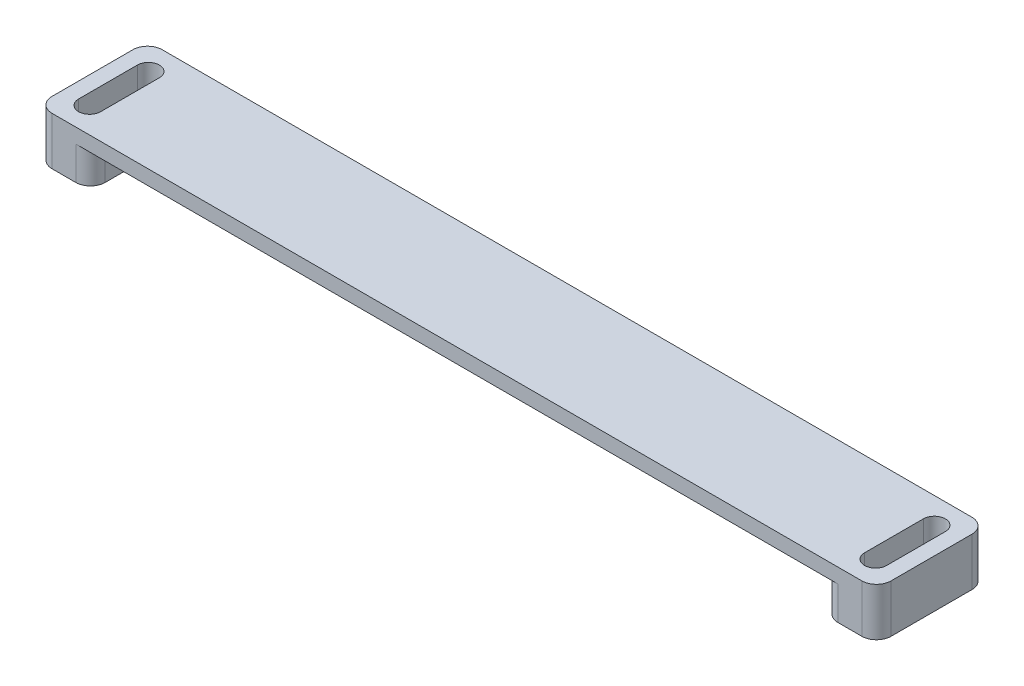
SolidWorks part; units mm, degrees
ref_plane "前视基准面" through (0, 0, 0) normal (0, 0, 1) x (1, 0, 0)
ref_plane "上视基准面" through (0, 0, 0) normal (0, 1, 0) x (1, 0, 0)
ref_plane "右视基准面" through (0, 0, 0) normal (1, 0, 0) x (0, 0, -1)
sketch "草图1" plane through (0, 0, 0) normal (0, 1, 0) x (1, 0, 0)
  line L1 (-48.5, -0.75) -> (48.5, -0.75)
  line L2 (-48.5, -0.75) -> (-48.5, 0.75)
  line L3 (-48.5, 0.75) -> (48.5, 0.75)
  line L4 (48.5, -0.75) -> (48.5, 0.75)
  line L5 (-48.5, -0.75) -> (48.5, 0.75) construction
  line L6 (-48.5, 0.75) -> (48.5, -0.75) construction
  line L10 (-48.5, -4.15) -> (48.5, -4.15)
  line L11 (-48.5, -4.15) -> (-48.5, -2.65)
  line L16 (-48.5, -2.65) -> (48.5, -2.65)
  line L17 (48.5, -4.15) -> (48.5, -2.65)
  line L18 (-48.5, -4.15) -> (48.5, -2.65) construction
  line L19 (-48.5, -2.65) -> (48.5, -4.15) construction
  line L20 (-48.5, -7.55) -> (48.5, -7.55)
  line L21 (-48.5, -7.55) -> (-48.5, -6.05)
  line L22 (-48.5, -6.05) -> (48.5, -6.05)
  line L23 (48.5, -7.55) -> (48.5, -6.05)
  line L24 (-48.5, -7.55) -> (48.5, -6.05) construction
  line L25 (-48.5, -6.05) -> (48.5, -7.55) construction
  point P0 (0, 0)
  point P7 (0, -3.4)
  point P12 (0, -6.8)
  dimension "D1" = 97
  dimension "D2" = 1.5
  dimension "D3" = 3
extrude "凸台-拉伸1" add sketch "草图1" along normal blind 2
sketch "草图2" plane through (0, 2, 0) normal (0, 1, 0) x (1, 0, 0)
  line L0 (48.5, 0.75) -> (-48.5, 0.75) construction
  line L1 (-57.115, -10.9) -> (57.115, -10.9)
  line L2 (-57.115, -10.9) -> (-57.115, 4.1)
  line L3 (-57.115, 4.1) -> (57.115, 4.1)
  line L4 (57.115, -10.9) -> (57.115, 4.1)
  line L5 (-57.115, -10.9) -> (57.115, 4.1) construction
  line L6 (-57.115, 4.1) -> (57.115, -10.9) construction
  point P0 (0, -3.4)
  point P5 (0, 0)
  point P8 (0, 0.75)
  dimension "D1" = 114.23
  dimension "D2" = 15
extrude "凸台-拉伸2" add sketch "草图2" along normal blind 2
sketch "草图3" plane through (0, 4, 0) normal (0, 1, 0) x (1, 0, 0)
  line L0 (-57.115, -3.4) -> (57.115, -3.4)
  line L1 (-57.115, 4.1) -> (-57.115, -10.9) construction
  line L2 (57.115, -10.9) -> (57.115, 4.1) construction
  line L3 (-53.5, -3.4) -> (-53.5, 4.1)
  line L4 (57.115, 4.1) -> (-57.115, 4.1) construction
  line L5 (53.5, -3.4) -> (53.5, 3.4133)
  line L6 (0, -3.4) -> (0, 20.1682) construction
  line L7 (-53.5, 0.6) -> (-53.5, -7.4) construction
  line L8 (-52, 0.6) -> (-52, -7.4)
  line L9 (-55, 0.6) -> (-55, -7.4)
  line L10 (53.5, -3.4) -> (53.5, 4.1)
  line L11 (53.5, 0.6) -> (53.5, -7.4) construction
  line L12 (52, 0.6) -> (52, -7.4)
  line L13 (55, 0.6) -> (55, -7.4)
  arc A2 (-52, 0.6) -> (-55, 0.6) centre (-53.5, 0.6) ccw
  arc A3 (-55, -7.4) -> (-52, -7.4) centre (-53.5, -7.4) ccw
  arc A4 (52, 0.6) -> (55, 0.6) centre (53.5, 0.6) cw
  arc A5 (55, -7.4) -> (52, -7.4) centre (53.5, -7.4) cw
  point P17 (-53.5, -3.4)
  point P25 (53.5, -3.4)
  dimension "D2" = 4
  dimension "D4" = 1.5
  dimension "D3" = 4
extrude "切除-拉伸1" cut sketch "草图3" against normal blind 10 contours L8 A2 L3 L0 | L3 A2 L9 L0 | L9 A3 L8 L0 | A5 L13 L0 L12 | A4 L5 L0 L13 | A4 L12 L0 L5
fillet "圆角1" radius 2 4 edges at (57.115, 3, -4.1) (57.115, 3, 10.9) (-57.115, 3, 10.9) (-57.115, 3, -4.1)
sketch "草图4" plane through (0, 2, 0) normal (0, -1, 0) x (1, 0, 0)
  line L0 (-53.5, 8.9) -> (-53.5, -2.1) construction
  line L1 (-52, 7.4) -> (-52, -0.6)
  line L2 (-49.885, 8.9) -> (-49.885, -2.1)
  line L3 (55, -0.6) -> (55, 7.4)
  line L4 (52, 7.4) -> (52, -0.6)
  line L5 (-55.115, -4.1) -> (55.115, -4.1)
  line L6 (57.115, -2.1) -> (57.115, 8.9)
  line L7 (55.115, 10.9) -> (-55.115, 10.9)
  line L8 (-57.115, 8.9) -> (-57.115, -2.1)
  line L9 (-55.115, -4.1) -> (55.115, -4.1)
  line L10 (57.115, -2.1) -> (57.115, 8.9)
  line L11 (55.115, 10.9) -> (-55.115, 10.9)
  line L12 (-57.115, 8.9) -> (-57.115, -2.1)
  line L37 (55, -0.6) -> (55, 7.4)
  line L38 (52, 7.4) -> (52, -0.6)
  line L39 (-52, -0.6) -> (-52, 7.4)
  line L40 (-55, 7.4) -> (-55, -0.6)
  line L41 (-52, -0.6) -> (-52, 7.4)
  line L42 (-55, 7.4) -> (-55, -0.6)
  line L43 (53.5, -4.1) -> (53.5, 8.9) construction
  line L44 (52, -0.6) -> (52, 7.4)
  line L45 (49.885, -2.1) -> (49.885, 8.9)
  arc A0 (-52, 7.4) -> (-55, 7.4) centre (-53.5, 7.4) ccw construction
  arc A1 (-55, -0.6) -> (-52, -0.6) centre (-53.5, -0.6) ccw construction
  arc A2 (-49.885, -2.1) -> (-51.885, -4.1) centre (-51.885, -2.1) cw
  arc A3 (-51.885, 10.9) -> (-49.885, 8.9) centre (-51.885, 8.9) cw
  arc A4 (55, 7.4) -> (52, 7.4) centre (53.5, 7.4) ccw
  arc A5 (52, -0.6) -> (55, -0.6) centre (53.5, -0.6) ccw
  arc A6 (55.115, -4.1) -> (57.115, -2.1) centre (55.115, -2.1) ccw
  arc A7 (57.115, 8.9) -> (55.115, 10.9) centre (55.115, 8.9) ccw
  arc A8 (-55.115, 10.9) -> (-57.115, 8.9) centre (-55.115, 8.9) ccw
  arc A9 (-57.115, -2.1) -> (-55.115, -4.1) centre (-55.115, -2.1) ccw
  arc A10 (55.115, -4.1) -> (57.115, -2.1) centre (55.115, -2.1) ccw
  arc A11 (57.115, 8.9) -> (55.115, 10.9) centre (55.115, 8.9) ccw
  arc A12 (-55.115, 10.9) -> (-57.115, 8.9) centre (-55.115, 8.9) ccw
  arc A13 (-57.115, -2.1) -> (-55.115, -4.1) centre (-55.115, -2.1) ccw
  arc A14 (55, 7.4) -> (52, 7.4) centre (53.5, 7.4) ccw
  arc A15 (52, -0.6) -> (55, -0.6) centre (53.5, -0.6) ccw
  arc A16 (-52, 7.4) -> (-55, 7.4) centre (-53.5, 7.4) ccw
  arc A17 (-55, -0.6) -> (-52, -0.6) centre (-53.5, -0.6) ccw
  arc A18 (-52, 7.4) -> (-55, 7.4) centre (-53.5, 7.4) ccw
  arc A19 (-55, -0.6) -> (-52, -0.6) centre (-53.5, -0.6) ccw
  arc A20 (49.885, 8.9) -> (51.885, 10.9) centre (51.885, 8.9) cw
  arc A21 (51.885, -4.1) -> (49.885, -2.1) centre (51.885, -2.1) cw
  arc M31 (-55, 7.4) -> (-52, 7.4) centre (-53.5, 7.4) cw
  line M32 (-52, 7.4) -> (-52, -0.6)
  arc M33 (-52, -0.6) -> (-55, -0.6) centre (-53.5, -0.6) cw
  line M34 (-55, -0.6) -> (-55, 7.4)
  arc M35 (52, 7.4) -> (55, 7.4) centre (53.5, 7.4) cw
  line M36 (55, 7.4) -> (55, -0.6)
  arc M37 (55, -0.6) -> (52, -0.6) centre (53.5, -0.6) cw
  line M38 (52, -0.6) -> (52, 7.4)
  line M43 (-55.115, -4.1) -> (55.115, -4.1)
  arc M44 (55.115, -4.1) -> (57.115, -2.1) centre (55.115, -2.1) ccw
  line M45 (57.115, -2.1) -> (57.115, 8.9)
  arc M46 (57.115, 8.9) -> (55.115, 10.9) centre (55.115, 8.9) ccw
  line M47 (55.115, 10.9) -> (-55.115, 10.9)
  arc M48 (-55.115, 10.9) -> (-57.115, 8.9) centre (-55.115, 8.9) ccw
  line M49 (-57.115, 8.9) -> (-57.115, -2.1)
  arc M50 (-57.115, -2.1) -> (-55.115, -4.1) centre (-55.115, -2.1) ccw
  dimension "D1" = 0
  dimension "D5" = 0
  dimension "D6" = 0
extrude "凸台-拉伸3" add sketch "草图4" along normal blind 4.54 contours A21 A20 L45 M43 M44 M45 M46 M47 M38 M35 M36 M37 | A3 L11 A2 L2 M48 M49 M50 M43 M34 M31 M32 M33
